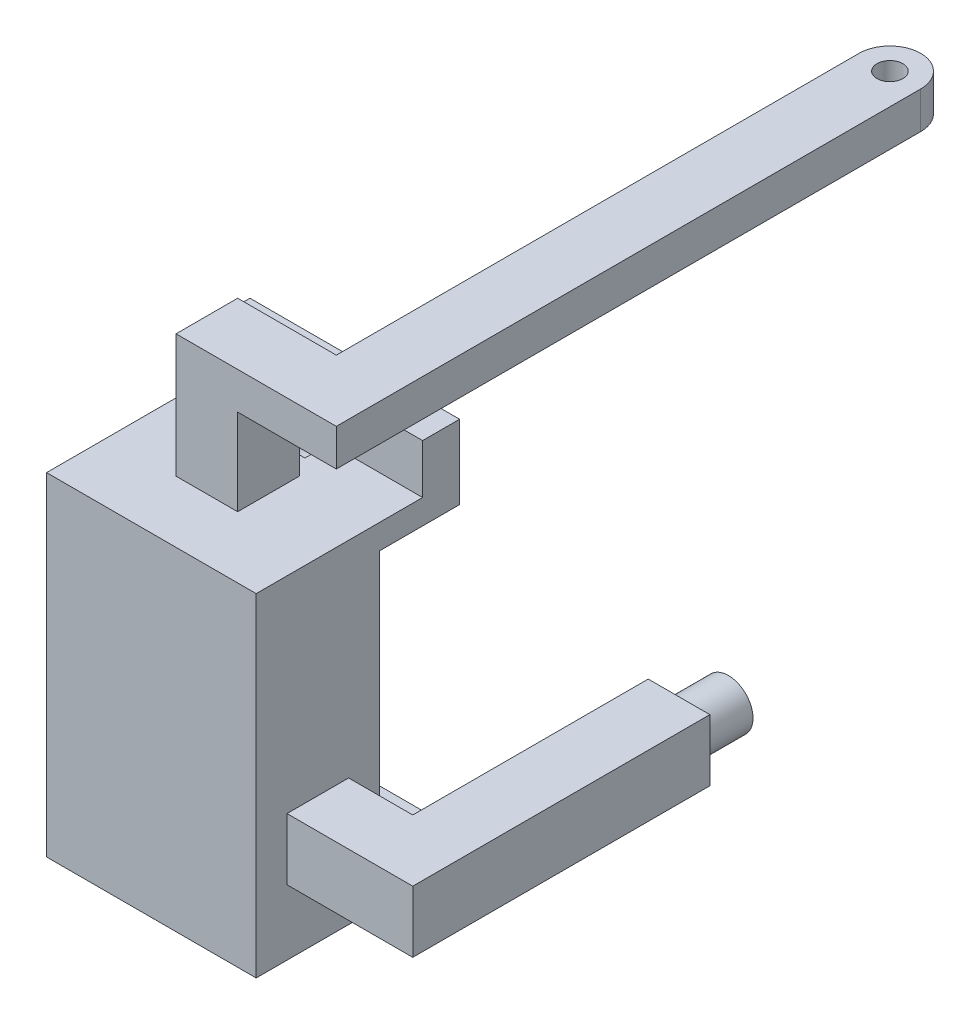
SolidWorks part; units mm, degrees
ref_plane "Front Plane" through (0, 0, 0) normal (0, 0, 1) x (1, 0, 0)
ref_plane "Top Plane" through (0, 0, 0) normal (0, 1, 0) x (1, 0, 0)
ref_plane "Right Plane" through (0, 0, 0) normal (1, 0, 0) x (0, 0, -1)
sketch "Sketch1" plane through (0, 0, 0) normal (0, 0, 1) x (1, 0, 0)
  line L1 (0, 0) -> (4.8, 0)
  line L2 (0, 0) -> (0, -4.8)
  line L3 (0, -4.8) -> (4.8, -4.8)
  line L4 (4.8, 0) -> (4.8, -4.8)
  dimension "D1" = 4.8
  dimension "D2" = 4.8
extrude "Boss-Extrude1" add sketch "Sketch1" along normal blind 1
sketch "Sketch2" plane through (0, 0, 0) normal (0, 0, -1) x (-1, 0, 0)
  line L0 (0, 0) -> (0, -4.8) construction
  line L1 (-5, 0.2) -> (0.2, 0.2)
  line L2 (-5, 0.2) -> (-5, -5)
  line L3 (-5, -5) -> (0.2, -5)
  line L4 (0.2, 0.2) -> (0.2, -5)
  line L5 (-5, 0.2) -> (0.2, -5) construction
  line L6 (-5, -5) -> (0.2, 0.2) construction
  line L7 (-4.8, 0) -> (0, 0) construction
  point P0 (-2.4, -2.4)
  dimension "D1" = 5.2
  dimension "D2" = 5.2
  dimension "D3" = 2.4
  dimension "D4" = 2.4
extrude "Boss-Extrude2" add sketch "Sketch2" along normal blind 50
sketch "Sketch3" plane through (0, 0, -50) normal (0, 0, -1) x (-1, 0, 0)
  line L0 (-5, -5) -> (0.2, -5) construction
  line L1 (-10.9, 11.1) -> (6.1, 11.1)
  line L2 (-10.9, 11.1) -> (-10.9, -15.9)
  line L3 (-10.9, -15.9) -> (6.1, -15.9)
  line L4 (6.1, 11.1) -> (6.1, -15.9)
  line L5 (-10.9, 11.1) -> (6.1, -15.9) construction
  line L6 (-10.9, -15.9) -> (6.1, 11.1) construction
  line L7 (0.2, -5) -> (0.2, 0.2) construction
  point P0 (-2.4, -2.4)
  dimension "D1" = 27
  dimension "D2" = 17
  dimension "D3" = 2.6
  dimension "D4" = 2.6
extrude "Boss-Extrude3" add sketch "Sketch3" along normal blind 10
sketch "Sketch4" plane through (0, 0, -60) normal (0, 0, -1) x (-1, 0, 0)
  line L0 (6.1, 11.1) -> (-10.9, 11.1) construction
  line L1 (4.1, 9.1) -> (-8.9, 9.1)
  line L2 (4.1, 9.1) -> (4.1, -13.9)
  line L3 (4.1, -13.9) -> (-8.9, -13.9)
  line L4 (-8.9, 9.1) -> (-8.9, -13.9)
  line L5 (4.1, 9.1) -> (-8.9, -13.9) construction
  line L6 (4.1, -13.9) -> (-8.9, 9.1) construction
  line L7 (6.1, -15.9) -> (6.1, 11.1) construction
  point P0 (-2.4, -2.4)
  dimension "D1" = 13
  dimension "D2" = 23
  dimension "D3" = 13.5
  dimension "D4" = 8.5
extrude "Cut-Extrude1" cut sketch "Sketch4" against normal blind 8.5
sketch "Sketch5" plane through (0, -15.9, 0) normal (0, -1, 0) x (1, 0, 0)
  line L2 (-3.1, -53) -> (-3.1, -57.5)
  line L3 (-3.1, -57.5) -> (7.9, -57.5)
  line L4 (7.9, -53) -> (7.9, -57.5)
  line L5 (10.9, -60) -> (-6.1, -60) construction
  line L6 (10.9, -60) -> (10.9, -50) construction
  line L7 (-6.1, -60) -> (-6.1, -50) construction
  line L8 (-3.1, -53) -> (7.9, -53)
  point P10 (10.9, -55)
  dimension "D1" = 2.5
  dimension "D2" = 3
  dimension "D3" = 3
  dimension "D4" = 4.5
extrude "Cut-Extrude2" cut sketch "Sketch5" against normal blind 4
sketch "Sketch6" plane through (0, 0.2, 0) normal (0, 1, 0) x (1, 0, 0)
  line L0 (5, 50) -> (5, 0) construction
  line L1 (-0.1, 40) -> (4.9, 40)
  line L2 (-0.1, 40) -> (-0.1, 35)
  line L3 (-0.1, 35) -> (4.9, 35)
  line L4 (4.9, 40) -> (4.9, 35)
  line L5 (-0.1, 40) -> (4.9, 35) construction
  line L6 (-0.1, 35) -> (4.9, 40) construction
  line L7 (-0.2, 50) -> (5, 50) construction
  point P0 (2.4, 37.5)
  dimension "D1" = 5
  dimension "D2" = 5
  dimension "D3" = 2.6
  dimension "D4" = 10
sketch "Sketch13" plane through (0, 0, -50) normal (0, 0, 1) x (1, 0, 0)
  line L1 (-6.1, 11.1) -> (10.9, 11.1)
  line L2 (-6.1, 11.1) -> (-6.1, -15.9)
  line L3 (-6.1, -15.9) -> (10.9, -15.9)
  line L4 (10.9, 11.1) -> (10.9, -15.9)
extrude "Cut-Extrude3" cut sketch "Sketch13" along normal through all
sketch "Sketch14" plane through (0, 0, -60) normal (0, 0, -1) x (-1, 0, 0)
  line L5 (6.1, -15.9) -> (6.1, 11.1) construction
  line L6 (-10.9, 11.1) -> (6.1, 11.1)
  line L7 (-10.9, 11.1) -> (-10.9, 9.1)
  line L8 (-10.9, 9.1) -> (6.1, 9.1)
  line L9 (6.1, 11.1) -> (6.1, 9.1)
  dimension "D1" = 2
extrude "Boss-Extrude5" add sketch "Sketch14" along normal blind 6.5
sketch "Sketch15" plane through (0, 11.1, 0) normal (0, 1, 0) x (1, 0, 0)
  line L0 (10.9, 66.5) -> (10.9, 50) construction
  line L1 (-6.1, 66.5) -> (10.9, 66.5)
  line L2 (-6.1, 66.5) -> (-6.1, 63.5)
  line L3 (-6.1, 63.5) -> (10.9, 63.5)
  line L4 (10.9, 66.5) -> (10.9, 63.5)
  dimension "D1" = 3
extrude "Boss-Extrude6" add sketch "Sketch15" along normal blind 4
sketch "Sketch16" plane through (0, 0, -66.5) normal (0, 0, -1) x (-1, 0, 0)
  line L0 (-10.9, 15.1) -> (-10.9, 9.1) construction
  line L1 (-10.9, 15.1) -> (6.1, 15.1) construction
  circle A0 centre (-2.4, 11.1) radius 0.95
  dimension "D3" = 1.9
  dimension "D1" = 8.5
  dimension "D2" = 4
extrude "Cut-Extrude4" cut sketch "Sketch16" against normal blind 5
ref_plane "Plane1" through (0, -2.4, 0) normal (0, -1, 0) x (-1, 0, 0)
mirror "Mirror2" about plane through (0, -2.4, 0) normal (0, -1, 0) of "Cut-Extrude4", "Boss-Extrude6", "Boss-Extrude5"
sketch "Sketch17" plane through (10.9, 0, 0) normal (1, 0, 0) x (0, 0, -1)
  line L0 (63.5, -15.9) -> (50, -15.9) construction
  line L1 (52.5, -5.6) -> (57.5, -5.6)
  line L2 (52.5, -5.6) -> (52.5, -10.6)
  line L3 (52.5, -10.6) -> (57.5, -10.6)
  line L4 (57.5, -5.6) -> (57.5, -10.6)
  line L5 (50, 11.1) -> (50, -15.9) construction
  dimension "D1" = 5.3
  dimension "D2" = 5
  dimension "D3" = 5
  dimension "D4" = 2.5
extrude "Boss-Extrude7" add sketch "Sketch17" along normal blind 10.2
sketch "Sketch18" plane through (0, 0, -57.5) normal (0, 0, -1) x (-1, 0, 0)
  line L0 (-21.1, -10.6) -> (-10.9, -10.6) construction
  line L1 (-21.1, -5.6) -> (-16.1, -5.6)
  line L2 (-21.1, -5.6) -> (-21.1, -10.6)
  line L3 (-21.1, -10.6) -> (-16.1, -10.6)
  line L4 (-16.1, -5.6) -> (-16.1, -10.6)
  dimension "D1" = 5
extrude "Boss-Extrude8" add sketch "Sketch18" along normal blind 23.1
sketch "Sketch19" plane through (0, 0, -80.6) normal (0, 0, -1) x (-1, 0, 0)
  line L1 (-21.1, -5.6) -> (-16.1, -5.6)
  line L2 (-21.1, -5.6) -> (-21.1, -10.6)
  line L3 (-21.1, -10.6) -> (-16.1, -10.6)
  line L4 (-16.1, -5.6) -> (-16.1, -10.6)
  circle A0 centre (-18.6, -8.1) radius 2
  point P8 (-21.1, -8.1)
  point P9 (-18.6, -10.6)
  dimension "D1" = 4
  dimension "D2" = 2.5
  dimension "D3" = 2.5
extrude "Cut-Extrude5" cut sketch "Sketch19" against normal blind 4 contours L2 L1 L4 L3 | A0
sketch "Sketch20" plane through (0, 0, -80.6) normal (0, 0, -1) x (-1, 0, 0)
  circle A0 centre (-18.6, -8.1) radius 0.5
  dimension "D1" = 1
extrude "Cut-Extrude6" cut sketch "Sketch20" against normal blind 4
sketch "Sketch21" plane through (0, 11.1, 0) normal (0, 1, 0) x (1, 0, 0)
  line L0 (-6.1, 63.5) -> (-6.1, 50) construction
  line L1 (-0.6, 60) -> (4.4, 60)
  line L2 (-0.6, 60) -> (-0.6, 55)
  line L3 (-0.6, 55) -> (4.4, 55)
  line L4 (4.4, 60) -> (4.4, 55)
  line L5 (-0.6, 60) -> (4.4, 55) construction
  line L6 (-0.6, 55) -> (4.4, 60) construction
  line L8 (-6.1, 50) -> (10.9, 50) construction
  point P0 (1.9, 57.5)
  dimension "D1" = 5
  dimension "D2" = 5
  dimension "D3" = 8
  dimension "D4" = 5
extrude "Boss-Extrude9" add sketch "Sketch21" along normal blind 10
sketch "Sketch22" plane through (0, 0, -60) normal (0, 0, -1) x (-1, 0, 0)
  line L0 (0.6, 21.1) -> (0.6, 11.1) construction
  line L1 (-4.4, 21.1) -> (0.6, 21.1)
  line L2 (-4.4, 21.1) -> (-4.4, 18.1)
  line L3 (-4.4, 18.1) -> (0.6, 18.1)
  line L4 (0.6, 21.1) -> (0.6, 18.1)
  dimension "D1" = 3
extrude "Boss-Extrude10" add sketch "Sketch22" along normal blind 42.402
sketch "Sketch23" plane through (0, 21.1, 0) normal (0, 1, 0) x (1, 0, 0)
  line L0 (-0.6, 102.402) -> (4.4, 102.402) construction
  circle A0 centre (1.9, 102.402) radius 2.5
extrude "Boss-Extrude11" add sketch "Sketch23" against normal blind 3
sketch "Sketch24" plane through (0, 21.1, 0) normal (0, 1, 0) x (1, 0, 0)
  circle A0 centre (1.9, 102.402) radius 1.05
  dimension "D1" = 2.1
extrude "Cut-Extrude7" cut sketch "Sketch24" against normal blind 3
sketch "Sketch26" plane through (0, 21.1, 0) normal (0, 1, 0) x (1, 0, 0)
  line L5 (10.9, 63.5) -> (10.9, 50) construction
  line L6 (-0.6, 55) -> (12.4, 55)
  line L7 (-0.6, 55) -> (-0.6, 60)
  line L8 (-0.6, 60) -> (12.4, 60)
  line L9 (12.4, 55) -> (12.4, 60)
  dimension "D1" = 5
  dimension "D2" = 1.5
extrude "Boss-Extrude12" add sketch "Sketch26" against normal blind 3
sketch "Sketch28" plane through (0, 0, -60) normal (0, 0, -1) x (-1, 0, 0)
  line L7 (-12.4, 21.1) -> (-4.4, 21.1) construction
  line L8 (-12.4, 18.1) -> (-7.4, 18.1)
  line L9 (-12.4, 18.1) -> (-12.4, 21.1)
  line L10 (-12.4, 21.1) -> (-7.4, 21.1)
  line L11 (-7.4, 18.1) -> (-7.4, 21.1)
  dimension "D1" = 5
extrude "Boss-Extrude13" add sketch "Sketch28" along normal blind 42.402
sketch "Sketch29" plane through (0, 21.1, 0) normal (0, 1, 0) x (1, 0, 0)
  line L1 (7.4, 102.402) -> (12.4, 102.402) construction
  circle A1 centre (9.9, 102.402) radius 2.5
extrude "Boss-Extrude14" add sketch "Sketch29" against normal blind 3
sketch "Sketch30" plane through (0, 21.1, 0) normal (0, 1, 0) x (1, 0, 0)
  circle A1 centre (9.9, 102.402) radius 1.05
  dimension "D1" = 2.1
extrude "Cut-Extrude8" cut sketch "Sketch30" against normal blind 3
sketch "Sketch32" plane through (4.4, 0, 0) normal (1, 0, 0) x (0, 0, -1)
  line L5 (60, 18.1) -> (104.902, 18.1)
  line L6 (60, 18.1) -> (60, 21.1)
  line L7 (60, 21.1) -> (104.902, 21.1)
  line L8 (104.902, 18.1) -> (104.902, 21.1)
extrude "Cut-Extrude9" cut sketch "Sketch32" against normal through all
